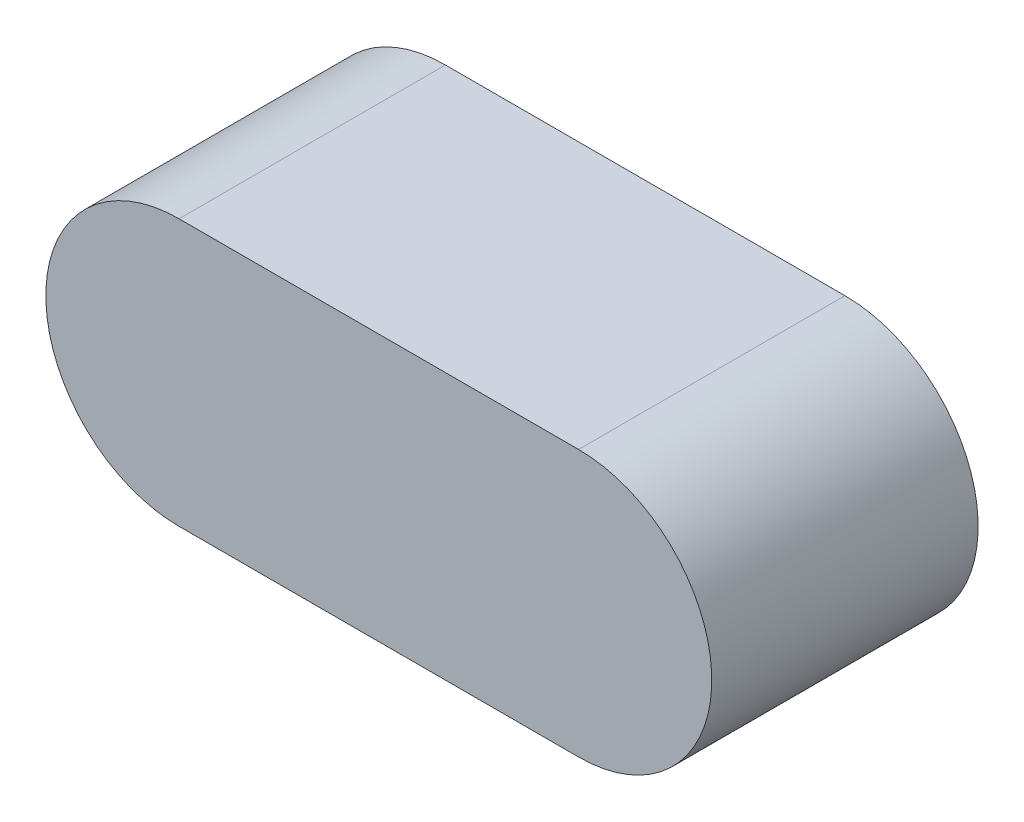
SolidWorks part; units mm, degrees
material "AISI Type A2 Tool Steel"
ref_plane "Front Plane" through (0, 0, 0) normal (0, 0, 1) x (1, 0, 0)
ref_plane "Top Plane" through (0, 0, 0) normal (0, 1, 0) x (1, 0, 0)
ref_plane "Right Plane" through (0, 0, 0) normal (1, 0, 0) x (0, 0, -1)
sketch "Sketch1" plane through (0, 0, 0) normal (0, 1, 0) x (1, 0, 0)
  line L0 (-5, 0) -> (5, 0) construction
  line L1 (-5, 2) -> (5, 2)
  line L2 (-5, 2) -> (-5, -2)
  line L3 (-5, -2) -> (5, -2)
  line L4 (5, 2) -> (5, -2)
  dimension "Square Size" = 4
  dimension "Length" = 10
extrude "Extrude1" add sketch "Sketch1" against normal blind 4
sketch "Sketch2" plane through (44.45, 6.35, 2) normal (0, 0, -1) x (-1, 0, 0)
  line L0 (41.45, -8.35) -> (47.45, -8.35) construction
  line L1 (41.45, -6.35) -> (47.45, -6.35)
  line L2 (41.45, -10.35) -> (47.45, -10.35)
  line L5 (49.45, -8.35) -> (47.45, -8.35) construction
  line L6 (41.45, -8.35) -> (39.45, -8.35) construction
  line L7 (39.45, -10.35) -> (39.45, -6.35) construction
  line L8 (49.45, -10.35) -> (49.45, -6.35) construction
  line L9 (39.45, -6.35) -> (49.45, -6.35) construction
  arc A0 (41.45, -6.35) -> (41.45, -10.35) centre (41.45, -8.35) ccw
  arc A1 (47.45, -10.35) -> (47.45, -6.35) centre (47.45, -8.35) ccw
  point P2 (44.45, -8.35)
extrude "Extrude2" cut sketch "Sketch2" along normal through all flip side to cut
ref_plane "Midplane" through (0, -2, 0) normal (0, 1, 0) x (1, 0, 0)
equation "\"Depth@Extrude1\" = \"Square Size@Sketch1\""
